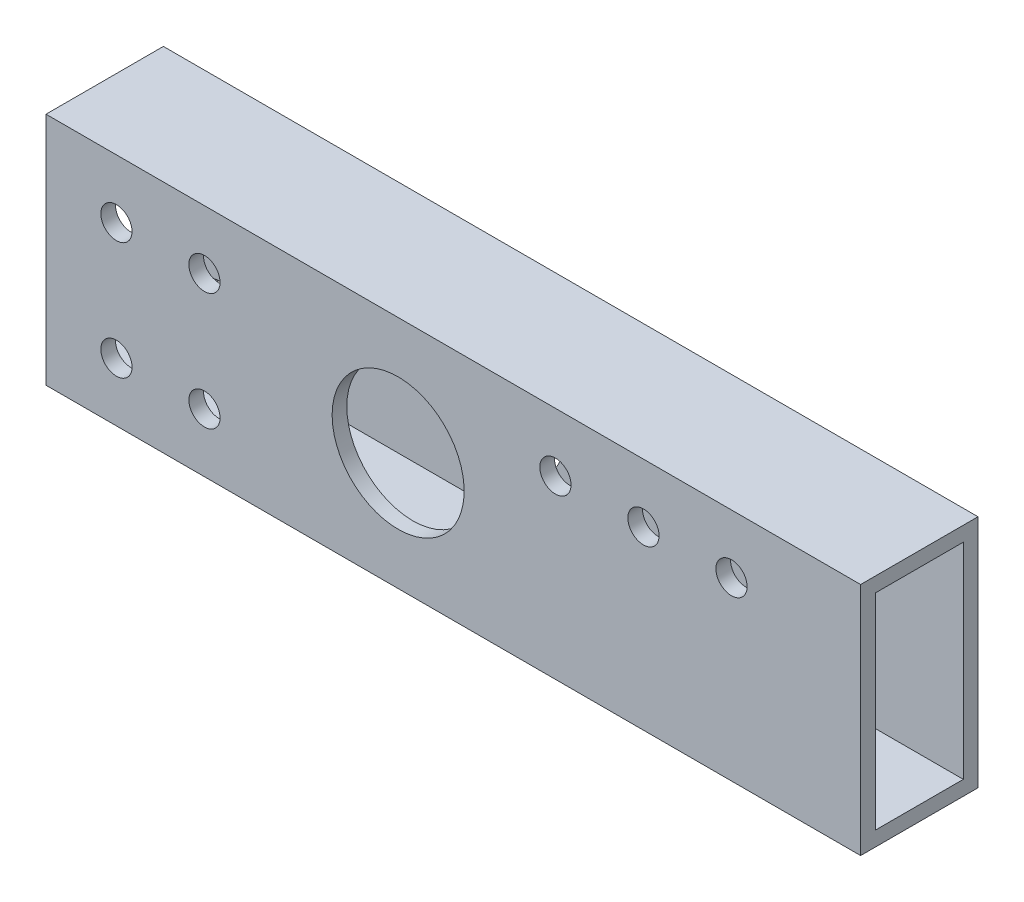
SolidWorks part; units mm, degrees
ref_plane "Front Plane" through (0, 0, 0) normal (0, 0, 1) x (1, 0, 0)
ref_plane "Top Plane" through (0, 0, 0) normal (0, 1, 0) x (1, 0, 0)
ref_plane "Right Plane" through (0, 0, 0) normal (1, 0, 0) x (0, 0, -1)
sketch "Sketch1" plane through (0, 0, 0) normal (0, 1, 0) x (1, 0, 0)
  line L1 (0, 0) -> (176.276, 0)
  line L2 (0, 0) -> (0, 25.4)
  line L3 (0, 25.4) -> (176.276, 25.4)
  line L4 (176.276, 0) -> (176.276, 25.4)
  dimension "D1" = 176.276
  dimension "D2" = 25.4
extrude "Boss-Extrude1" add sketch "Sketch1" along normal blind 50.8
sketch "Sketch2" plane through (176.276, 0, 0) normal (1, 0, 0) x (0, 0, -1)
  line L0 (3.175, 47.625) -> (3.175, 3.175)
  line L1 (0, 50.8) -> (25.4, 50.8)
  line L2 (0, 50.8) -> (0, 0)
  line L3 (0, 0) -> (25.4, 0)
  line L4 (25.4, 50.8) -> (25.4, 0)
  line L5 (3.175, 3.175) -> (22.225, 3.175)
  line L6 (22.225, 47.625) -> (22.225, 3.175)
  line L7 (3.175, 47.625) -> (22.225, 47.625)
  dimension "D1" = 3.175
extrude "Cut-Extrude1" cut sketch "Sketch2" against normal through all flip side to cut
sketch "Sketch3" plane through (0, 0, -25.4) normal (0, 0, -1) x (-1, 0, 0)
  line L1 (-176.276, 50.8) -> (0, 50.8) construction
  line L2 (0, 50.8) -> (0, 0) construction
  circle A0 centre (-76.2, 25.4) radius 14.2875
  dimension "D1" = 28.575
  dimension "D4" = 76.2
  dimension "D3" = 25.4
extrude "Cut-Extrude2" cut sketch "Sketch3" against normal through all
sketch "Sketch4" plane through (0, 0, 0) normal (0, 0, 1) x (1, 0, 0)
  line L0 (176.276, 50.8) -> (176.276, 0) construction
  line L2 (0, 50.8) -> (176.276, 50.8) construction
  circle A0 centre (148.336, 38.1) radius 3.3782
  circle A1 centre (129.286, 38.1) radius 3.3782
  circle A2 centre (110.236, 38.1) radius 3.3782
  dimension "D1" = 6.7564
  dimension "D2" = 6.7564
  dimension "D3" = 6.7564
  dimension "D4" = 27.94
  dimension "D5" = 19.05
  dimension "D6" = 19.05
  dimension "D7" = 12.7
  dimension "D8" = 12.7
  dimension "D9" = 12.7
extrude "Cut-Extrude3" cut sketch "Sketch4" against normal through all
sketch "Sketch5" plane through (0, 0, 0) normal (0, 0, 1) x (1, 0, 0)
  line L0 (0, 50.8) -> (0, 0) construction
  line L1 (0, 0) -> (176.276, 0) construction
  line L2 (0, 50.8) -> (176.276, 50.8) construction
  circle A0 centre (15.24, 38.1) radius 3.3782
  circle A1 centre (15.24, 12.7) radius 3.3782
  circle A2 centre (34.29, 12.7) radius 3.3782
  circle A3 centre (34.29, 38.1) radius 3.3782
  dimension "D5" = 6.7564
  dimension "D6" = 6.7564
  dimension "D7" = 6.7564
  dimension "D8" = 6.7564
  dimension "D1" = 15.24
  dimension "D2" = 19.05
  dimension "D3" = 15.24
  dimension "D4" = 19.05
  dimension "D9" = 12.7
  dimension "D10" = 12.7
  dimension "D11" = 12.7
  dimension "D12" = 12.7
extrude "Cut-Extrude4" cut sketch "Sketch5" against normal through all
